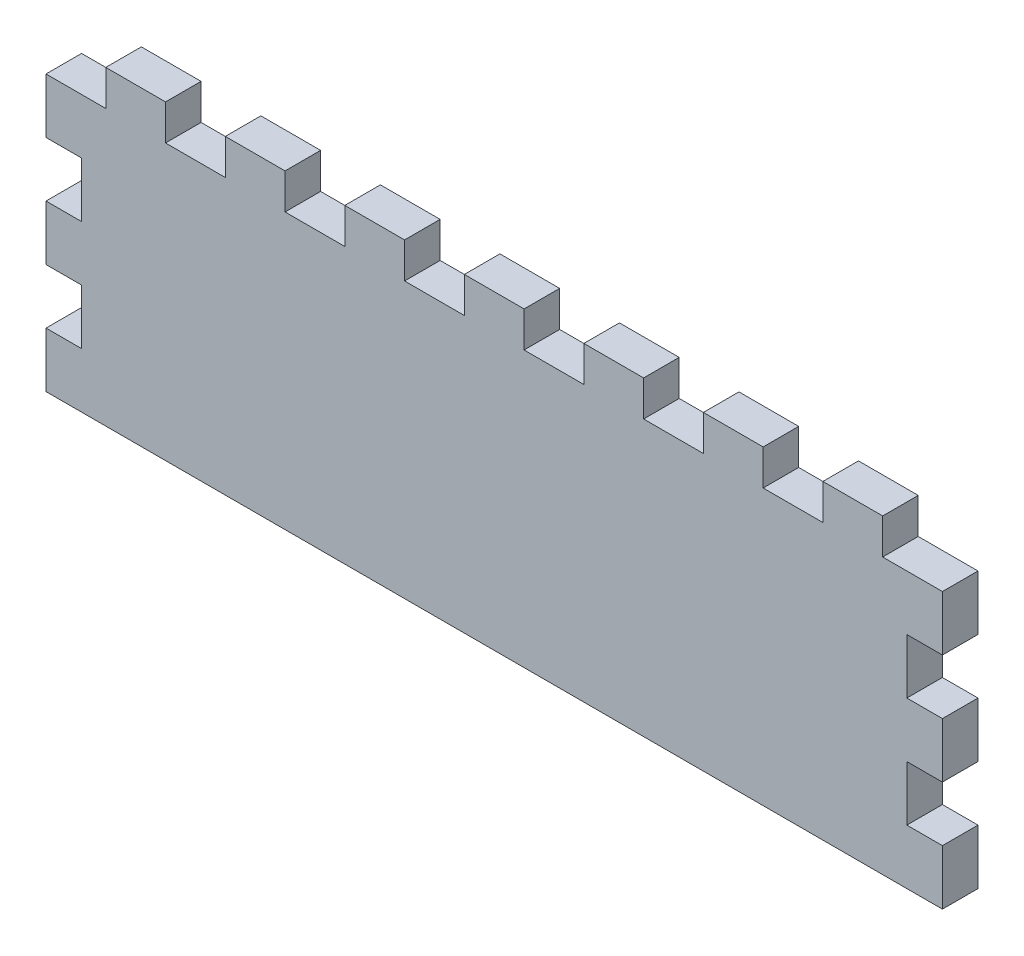
SolidWorks part; units mm, degrees
material "Acrylic (Medium-high impact)"
ref_plane "Front Plane" through (0, 0, 0) normal (0, 0, 1) x (1, 0, 0)
ref_plane "Top Plane" through (0, 0, 0) normal (0, 1, 0) x (1, 0, 0)
ref_plane "Right Plane" through (0, 0, 0) normal (1, 0, 0) x (0, 0, -1)
sketch "Sketch1" plane through (0, 0, 0) normal (0, 0, 1) x (1, 0, 0)
  line L1 (-40, -40) -> (40, -40)
  line L2 (-40, -40) -> (-40, 40)
  line L3 (-40, 40) -> (40, 40)
  line L4 (40, -40) -> (40, 40)
  line L5 (-40, -40) -> (40, 40) construction
  line L6 (-40, 40) -> (40, -40) construction
  point P0 (0, 0)
  dimension "D1" = 80
  dimension "D2" = 80
extrude "Boss-Extrude1" add sketch "Sketch1" along normal blind 3.175
sketch "Sketch3" plane through (0, 0, 3.175) normal (0, 0, 1) x (1, 0, 0)
  line L1 (-34.6667, -36.825) -> (-34.6667, -40)
  line L2 (-40, -36.825) -> (-34.6667, -36.825)
  line L3 (-29.3333, -36.825) -> (-29.3333, -40)
  line L4 (-29.3333, -36.825) -> (-24, -36.825)
  line L5 (-34.6667, -40) -> (-29.3333, -40)
  line L6 (-24, -36.825) -> (-24, -40)
  line L7 (-24, -40) -> (-18.6667, -40)
  line L8 (-18.6667, -36.825) -> (-18.6667, -40)
  line L9 (-18.6667, -36.825) -> (-13.3333, -36.825)
  line L10 (-13.3333, -36.825) -> (-13.3333, -40)
  line L11 (-13.3333, -40) -> (-8, -40)
  line L12 (-8, -36.825) -> (-8, -40)
  line L13 (-8, -36.825) -> (-2.6667, -36.825)
  line L14 (-2.6667, -36.825) -> (-2.6667, -40)
  line L15 (-2.6667, -40) -> (2.6667, -40)
  line L16 (2.6667, -36.825) -> (2.6667, -40)
  line L17 (2.6667, -36.825) -> (8, -36.825)
  line L18 (8, -36.825) -> (8, -40)
  line L19 (8, -40) -> (13.3333, -40)
  line L20 (13.3333, -36.825) -> (13.3333, -40)
  line L21 (13.3333, -36.825) -> (18.6667, -36.825)
  line L22 (18.6667, -36.825) -> (18.6667, -40)
  line L23 (18.6667, -40) -> (24, -40)
  line L24 (24, -36.825) -> (24, -40)
  line L25 (24, -36.825) -> (29.3333, -36.825)
  line L26 (29.3333, -36.825) -> (29.3333, -40)
  line L27 (29.3333, -40) -> (34.6667, -40)
  line L28 (34.6667, -40) -> (34.6667, -36.825)
  line L29 (34.6667, -36.825) -> (40, -36.825)
  line L31 (0, 0) -> (50000, 0) construction
  line L32 (34.6667, 36.825) -> (40, 36.825)
  line L33 (40, -40) -> (40, 40) construction
  line L34 (34.6667, 40) -> (34.6667, 36.825)
  line L35 (29.3333, 40) -> (34.6667, 40)
  line L36 (29.3333, 36.825) -> (29.3333, 40)
  line L37 (24, 36.825) -> (29.3333, 36.825)
  line L38 (24, 36.825) -> (24, 40)
  line L39 (18.6667, 40) -> (24, 40)
  line L40 (18.6667, 36.825) -> (18.6667, 40)
  line L41 (13.3333, 36.825) -> (18.6667, 36.825)
  line L42 (13.3333, 36.825) -> (13.3333, 40)
  line L43 (8, 40) -> (13.3333, 40)
  line L44 (8, 36.825) -> (8, 40)
  line L45 (2.6667, 36.825) -> (8, 36.825)
  line L46 (2.6667, 36.825) -> (2.6667, 40)
  line L47 (-2.6667, 40) -> (2.6667, 40)
  line L48 (-2.6667, 36.825) -> (-2.6667, 40)
  line L49 (-8, 36.825) -> (-2.6667, 36.825)
  line L50 (-8, 36.825) -> (-8, 40)
  line L51 (-13.3333, 40) -> (-8, 40)
  line L52 (-13.3333, 36.825) -> (-13.3333, 40)
  line L53 (-18.6667, 36.825) -> (-13.3333, 36.825)
  line L54 (-18.6667, 36.825) -> (-18.6667, 40)
  line L55 (-24, 40) -> (-18.6667, 40)
  line L56 (-24, 36.825) -> (-24, 40)
  line L57 (-34.6667, 40) -> (-29.3333, 40)
  line L58 (-29.3333, 36.825) -> (-24, 36.825)
  line L59 (-29.3333, 36.825) -> (-29.3333, 40)
  line L60 (-40, 36.825) -> (-34.6667, 36.825)
  line L61 (-34.6667, 36.825) -> (-34.6667, 40)
  line L64 (40, 27.005) -> (40, 22.095)
  line L65 (40, 31.915) -> (36.825, 31.915)
  line L66 (36.825, 31.915) -> (36.825, 27.005)
  line L67 (36.825, 27.005) -> (40, 27.005)
  line L69 (40, 22.095) -> (36.825, 22.095)
  line L70 (36.825, 22.095) -> (36.825, 17.185)
  line L71 (36.825, 17.185) -> (40, 17.185)
  line L72 (40, 17.185) -> (40, 12.275)
  line L73 (40, 12.275) -> (36.825, 12.275)
  line L74 (36.825, 12.275) -> (36.825, 7.365)
  line L75 (36.825, 7.365) -> (40, 7.365)
  line L76 (40, 7.365) -> (40, 2.455)
  line L77 (40, 2.455) -> (36.825, 2.455)
  line L78 (36.825, 2.455) -> (36.825, -2.455)
  line L79 (36.825, -2.455) -> (40, -2.455)
  line L80 (40, -2.455) -> (40, -7.365)
  line L81 (40, -7.365) -> (36.825, -7.365)
  line L82 (36.825, -7.365) -> (36.825, -12.275)
  line L83 (36.825, -12.275) -> (40, -12.275)
  line L84 (40, -12.275) -> (40, -17.185)
  line L85 (40, -17.185) -> (36.825, -17.185)
  line L86 (36.825, -17.185) -> (36.825, -22.095)
  line L87 (36.825, -22.095) -> (40, -22.095)
  line L88 (40, -22.095) -> (40, -27.005)
  line L89 (40, -27.005) -> (36.825, -27.005)
  line L90 (36.825, -27.005) -> (36.825, -31.915)
  line L91 (36.825, -31.915) -> (40, -31.915)
  line L92 (40, -31.915) -> (40, -36.825)
  line L93 (0, 0) -> (0, 50000) construction
  line L94 (0, 0) -> (-50000, 0) construction
  line L95 (-40, -31.915) -> (-40, -36.825)
  line L96 (-36.825, -31.915) -> (-40, -31.915)
  line L97 (-36.825, -27.005) -> (-36.825, -31.915)
  line L98 (-40, -27.005) -> (-36.825, -27.005)
  line L99 (-40, -22.095) -> (-40, -27.005)
  line L100 (-36.825, -22.095) -> (-40, -22.095)
  line L101 (-36.825, -17.185) -> (-36.825, -22.095)
  line L102 (-40, -17.185) -> (-36.825, -17.185)
  line L103 (-40, -12.275) -> (-40, -17.185)
  line L104 (-36.825, -12.275) -> (-40, -12.275)
  line L105 (-36.825, -7.365) -> (-36.825, -12.275)
  line L106 (-40, -7.365) -> (-36.825, -7.365)
  line L107 (-40, -2.455) -> (-40, -7.365)
  line L108 (-36.825, -2.455) -> (-40, -2.455)
  line L109 (-36.825, 2.455) -> (-36.825, -2.455)
  line L110 (-40, 2.455) -> (-36.825, 2.455)
  line L111 (-40, 7.365) -> (-40, 2.455)
  line L112 (-36.825, 7.365) -> (-40, 7.365)
  line L113 (-36.825, 12.275) -> (-36.825, 7.365)
  line L114 (-40, 12.275) -> (-36.825, 12.275)
  line L115 (-40, 17.185) -> (-40, 12.275)
  line L116 (-36.825, 17.185) -> (-40, 17.185)
  line L117 (-36.825, 22.095) -> (-36.825, 17.185)
  line L118 (-40, 22.095) -> (-36.825, 22.095)
  line L119 (-40, 36.825) -> (-40, 31.915)
  line L120 (-36.825, 27.005) -> (-40, 27.005)
  line L121 (-36.825, 31.915) -> (-36.825, 27.005)
  line L122 (-40, 31.915) -> (-36.825, 31.915)
  line L123 (-40, 27.005) -> (-40, 22.095)
extrude "Cut-Extrude2" cut sketch "Sketch3" against normal through all and the other way through all
sketch "Sketch4" plane through (0, 0, 3.175) normal (0, 0, 1) x (1, 0, 0)
  line L1 (-40, 12.275) -> (40.3518, 12.275)
  line L2 (-40, 12.275) -> (-40, -40.0938)
  line L3 (-40, -40.0938) -> (40.3518, -40.0938)
  line L4 (40.3518, 12.275) -> (40.3518, -40.0938)
extrude "Cut-Extrude3" cut sketch "Sketch4" against normal through all
